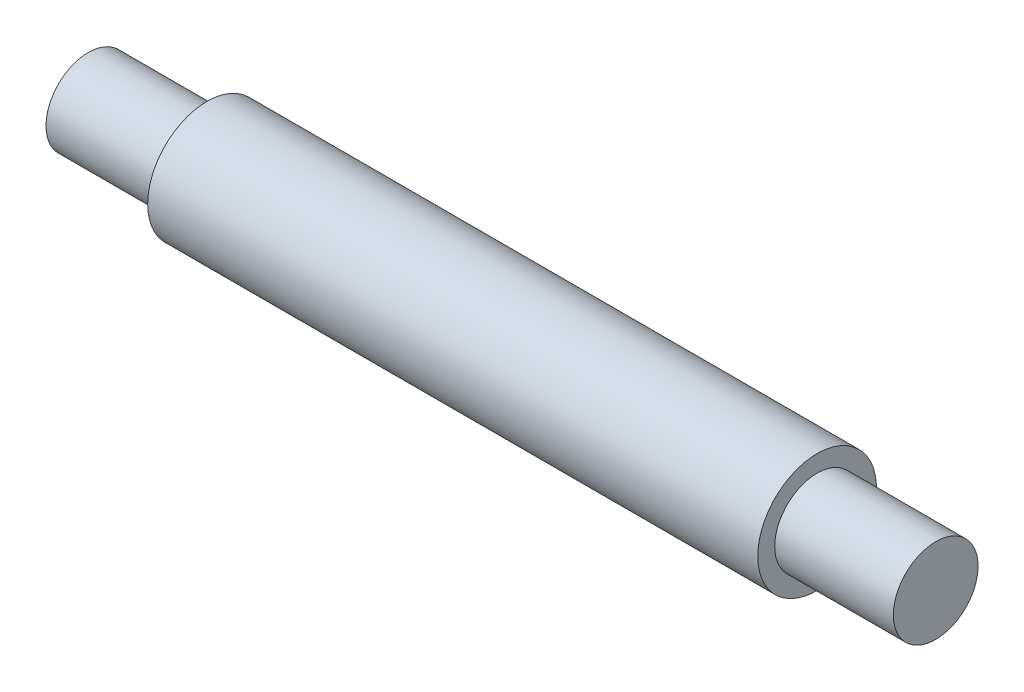
SolidWorks part; units mm, degrees
ref_plane "Front Plane" through (0, 0, 0) normal (0, 0, 1) x (1, 0, 0)
ref_plane "Top Plane" through (0, 0, 0) normal (0, 1, 0) x (1, 0, 0)
ref_plane "Right Plane" through (0, 0, 0) normal (1, 0, 0) x (0, 0, -1)
sketch "Sketch1" plane through (0, 0, 0) normal (0, 1, 0) x (1, 0, 0)
  line L0 (47, 1.5) -> (40, 1.5)
  line L1 (4, 1.5) -> (4, 0.5)
  line L2 (4, 0.5) -> (40, 0.5)
  line L3 (40, 0.5) -> (40, 1.5)
  line L5 (47, 1.5) -> (47, 4)
  line L9 (4, 1.5) -> (-3, 1.5)
  line L10 (-3, 1.5) -> (-3, 4)
  line L11 (-3, 4) -> (47, 4)
  dimension "D2" = 7
  dimension "D3" = 7
  dimension "D4" = 1
  dimension "D5" = 36
  dimension "D9" = 2.5
  dimension "D11" = 2.5
revolve "Revolve1" add sketch "Sketch1" angle 360 about L11
